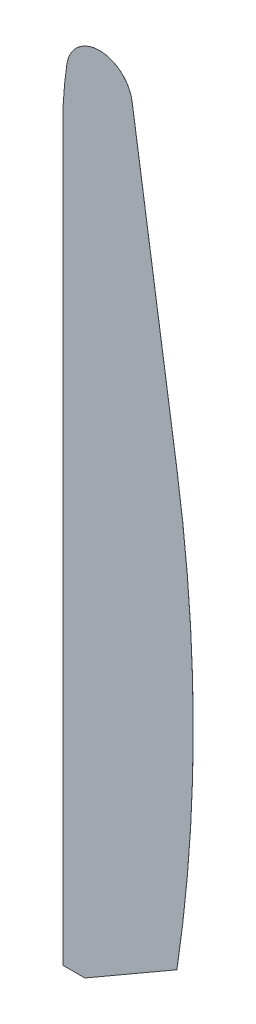
SolidWorks part; units mm, degrees
ref_plane "Front Plane" through (0, 0, 0) normal (1, 0, 0) x (0, 1, 0)
ref_plane "Top Plane" through (0, 0, 0) normal (0, 0, 1) x (0, 1, 0)
ref_plane "Right Plane" through (0, 0, 0) normal (0, 1, 0) x (-1, 0, 0)
sketch "Sketch1" plane through (0, 0, 0) normal (0, 0, 1) x (0, 1, 0)
  line L0 (0, 0) -> (0, 50000) construction
  line L1 (0, 0) -> (50000, 0) construction
  line L2 (143.5634, 601.065) -> (1381.2364, 932.6984) construction
  line L3 (0, 0) -> (165.075, 0)
  line L4 (0, 0) -> (0, -5)
  line L5 (0, -5) -> (12.0582, -25.8854)
  line L6 (177.5, -15.7264) -> (110.3647, -25.8854)
  line L7 (0, 0) -> (61.2115, -29.5833)
  line L8 (0, 0) -> (177.5, -15.7264)
  arc A0 (165.075, 0) -> (177.5, -0.9348) centre (165.075, -83.0449) cw
  arc A1 (177.5, -0.9348) -> (177.5, -15.7264) centre (176.3809, -8.3306) cw
  arc A2 (12.0582, -25.8854) -> (110.3647, -25.8854) centre (61.2115, 298.942) ccw
  point P17 (82.8897, -18.9583)
  point P18 (107.3445, -18.9583)
  point P19 (129.1347, -13.0565)
  point P20 (180, -15.7052)
  point P21 (61.0038, -30)
  point P22 (0, 0)
  point P23 (-122.3366, 85.932)
  dimension "D1" = 5
  dimension "D2" = 25.8854
  dimension "D3" = 165.075
  dimension "Span" = 177.5
  dimension "Chord" = 29.5833
  dimension "D4" = 30
  dimension "D5" = 14.7917
extrude "Boss-Extrude1" add sketch "Sketch1" along normal blind 0.01 contours L6 A2 L5 L4 L3 A0 A1
equation "\"D3@Sketch1\"=\"Span@Sketch1\"*0.93"
equation "\"D2@Sketch1\"=\"Chord@Sketch1\"*0.875"
equation "\"Chord@Sketch1\"=\"Span@Sketch1\"/6"
equation "\"D5@Sketch1\"=\"Chord@Sketch1\"/2"
